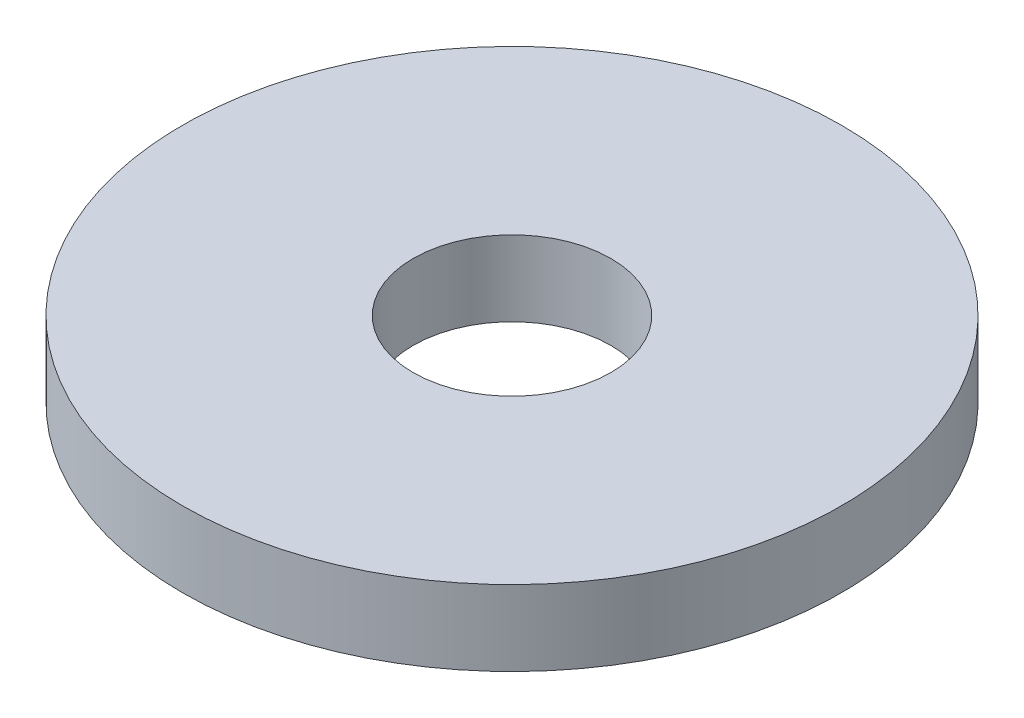
SolidWorks part; units mm, degrees
ref_plane "正面" through (0, 0, 0) normal (0, 0, 1) x (1, 0, 0)
ref_plane "平面" through (0, 0, 0) normal (0, 1, 0) x (1, 0, 0)
ref_plane "右側面" through (0, 0, 0) normal (1, 0, 0) x (0, 0, -1)
sketch "ｽｹｯﾁ2" plane through (0, 0, 0) normal (0, 1, 0) x (-1, 0, 0)
  circle A0 centre (0, 0) radius 7
  circle A2 centre (0, 0) radius 2.1
  dimension "D1" = 14
  dimension "D2" = 4.2
extrude "ﾎﾞｽ - 押し出し2" add sketch "ｽｹｯﾁ2" along normal blind 1.6
